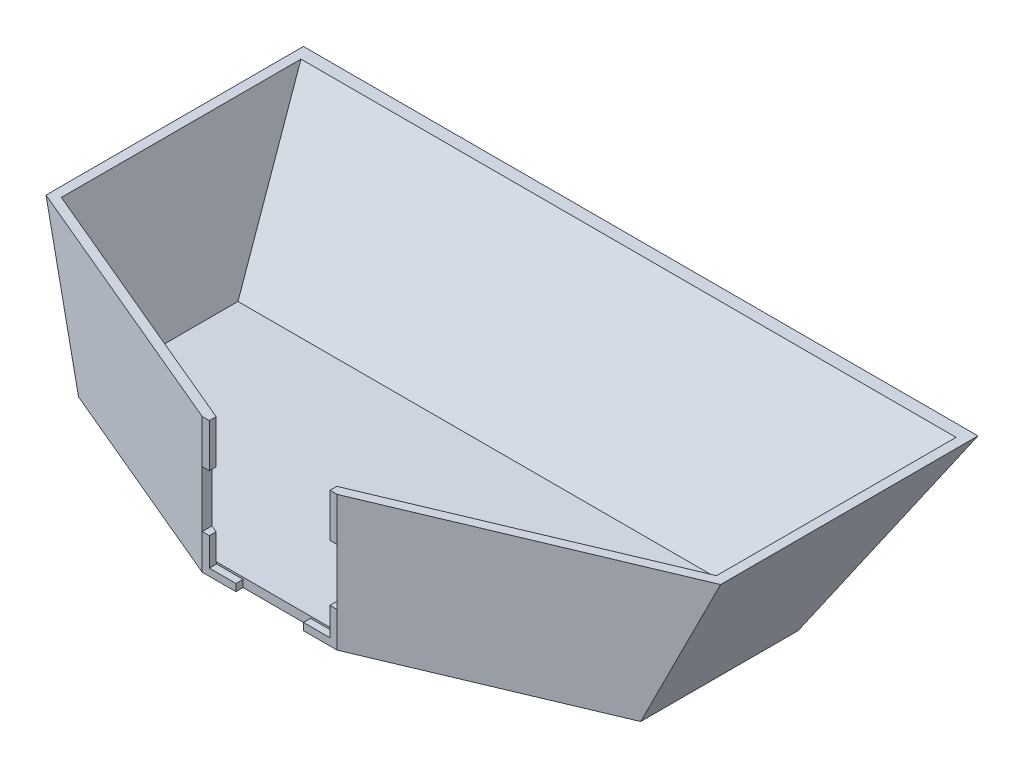
SolidWorks part; units mm, degrees
ref_plane "Front Plane" through (0, 0, 0) normal (0, 0, 1) x (1, 0, 0)
ref_plane "Top Plane" through (0, 0, 0) normal (0, 1, 0) x (1, 0, 0)
ref_plane "Right Plane" through (0, 0, 0) normal (1, 0, 0) x (0, 0, -1)
sketch "Sketch1" plane through (0, 0, 0) normal (0, 1, 0) x (1, 0, 0)
  line L0 (0, 0) -> (0, -68.0967) construction
  line L2 (125, -35) -> (125, 35)
  line L3 (125, 35) -> (-125, 35)
  line L4 (-125, -35) -> (-125, 35)
  line L5 (125, -35) -> (-125, 35) construction
  line L6 (125, 35) -> (-125, -35) construction
  line L7 (125, -35) -> (30, -75)
  line L8 (-125, -35) -> (-30, -75)
  line L9 (-30, -75) -> (30, -75)
  point P0 (0, 0)
  dimension "D1" = 250
  dimension "D2" = 70
  dimension "D3" = 30
ref_plane "Plane1" through (0, 60, 0) normal (0, 1, 0) x (1, 0, 0)
sketch "Sketch2" plane through (0, 60, 0) normal (0, 1, 0) x (1, 0, 0)
  line L0 (0, 0) -> (0, 61.1496) construction
  line L2 (-150, -24.4737) -> (-150, 90)
  line L3 (-150, 90) -> (150, 90)
  line L4 (150, -24.4737) -> (150, 90)
  line L5 (125, 35) -> (-125, -35) construction
  line L10 (-30, -75) -> (-150, -24.4737)
  line L11 (-125, -35) -> (-30, -75) construction
  line L12 (30, -75) -> (150, -24.4737)
  line L13 (-30, -75) -> (30, -75)
  dimension "D1" = 300
loft "Loft2" add profiles "Sketch2", "Sketch1"
shell "Shell2" thickness 4
sketch "Sketch5" plane through (0, 0, 75) normal (0, 0, 1) x (1, 0, 0)
  line L0 (-40.1086, 28.175) -> (53.077, 28.175) construction
  line L1 (-26.825, 3.175) -> (-15, 3.175)
  line L2 (-26.825, 3.175) -> (-26.825, 15.675)
  line L3 (-26.825, 60) -> (26.825, 60)
  line L4 (26.825, 3.175) -> (26.825, 15.675)
  line L5 (90.7501, 60) -> (-90.7501, 60) construction
  line L6 (30, 15.675) -> (30, 40.675)
  line L7 (-26.825, 15.675) -> (-30, 15.675)
  line L9 (-30, 0) -> (30, 0) construction
  line L10 (-15, 0) -> (-15, 3.175)
  line L11 (0, 0) -> (0, 32.3358) construction
  line L12 (15, 0) -> (15, 3.175)
  line L13 (15, 3.175) -> (26.825, 3.175)
  line L14 (-15, 0) -> (15, 0)
  line L15 (-26.825, 40.675) -> (-30, 40.675)
  line L16 (-30, 15.675) -> (-30, 40.675)
  line L17 (26.825, 40.675) -> (30, 40.675)
  line L19 (26.825, 15.675) -> (30, 15.675)
  line L20 (-26.825, 40.675) -> (-26.825, 60)
  line L21 (26.825, 40.675) -> (26.825, 60)
  dimension "D1" = 53.65
  dimension "D2" = 28.175
  dimension "D3" = 3.175
  dimension "D4" = 15
  dimension "D5" = 25
  dimension "D6" = 3.175
extrude "Cut-Extrude1" cut sketch "Sketch5" against normal blind 3.175
sketch "Sketch6" plane through (0, 0, 71.825) normal (0, 0, 1) x (1, 0, 0)
  line L4 (-27.2329, 15.675) -> (-27.2329, 40.675)
  line L5 (-27.2329, 40.675) -> (-30, 40.675)
  line L6 (-30, 40.675) -> (-30, 15.675)
  line L7 (-30, 15.675) -> (-27.2329, 15.675)
  line L8 (-27.2329, 15.675) -> (-27.2329, 40.675)
  line L9 (-27.2329, 40.675) -> (-30, 40.675)
  line L10 (-30, 40.675) -> (-30, 15.675)
  line L11 (-30, 15.675) -> (-27.2329, 15.675)
  line L16 (27.2329, 40.675) -> (27.2329, 15.675)
  line L17 (27.2329, 15.675) -> (30, 15.675)
  line L18 (30, 15.675) -> (30, 40.675)
  line L19 (30, 40.675) -> (27.2329, 40.675)
  line L20 (27.2329, 40.675) -> (27.2329, 15.675)
  line L21 (27.2329, 15.675) -> (30, 15.675)
  line L22 (30, 15.675) -> (30, 40.675)
  line L23 (30, 40.675) -> (27.2329, 40.675)
  dimension "D1" = 0
  dimension "D2" = 0
extrude "Cut-Extrude2" cut sketch "Sketch6" against normal blind 10
